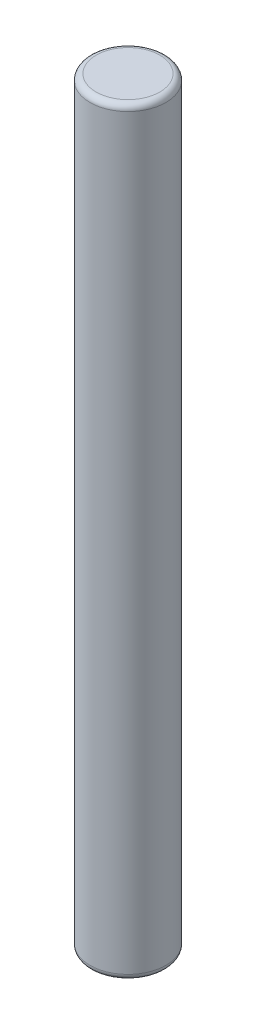
SolidWorks part; units mm, degrees
ref_plane "Front Plane" through (0, 0, 0) normal (0, 0, 1) x (1, 0, 0)
ref_plane "Top Plane" through (0, 0, 0) normal (0, 1, 0) x (1, 0, 0)
ref_plane "Right Plane" through (0, 0, 0) normal (1, 0, 0) x (0, 0, -1)
sketch "Sketch1" plane through (0, 0, 0) normal (0, 1, 0) x (1, 0, 0)
  circle A0 centre (0, 0) radius 1.5875
  dimension "D1" = 3.175
extrude "Boss-Extrude1" add sketch "Sketch1" along normal blind 31.75
fillet "Fillet2" radius 0.254 1 edges at (0, 31.75, 1.5875)
fillet "Fillet3" radius 0.254 1 edges at (0, 0, 1.5875)
